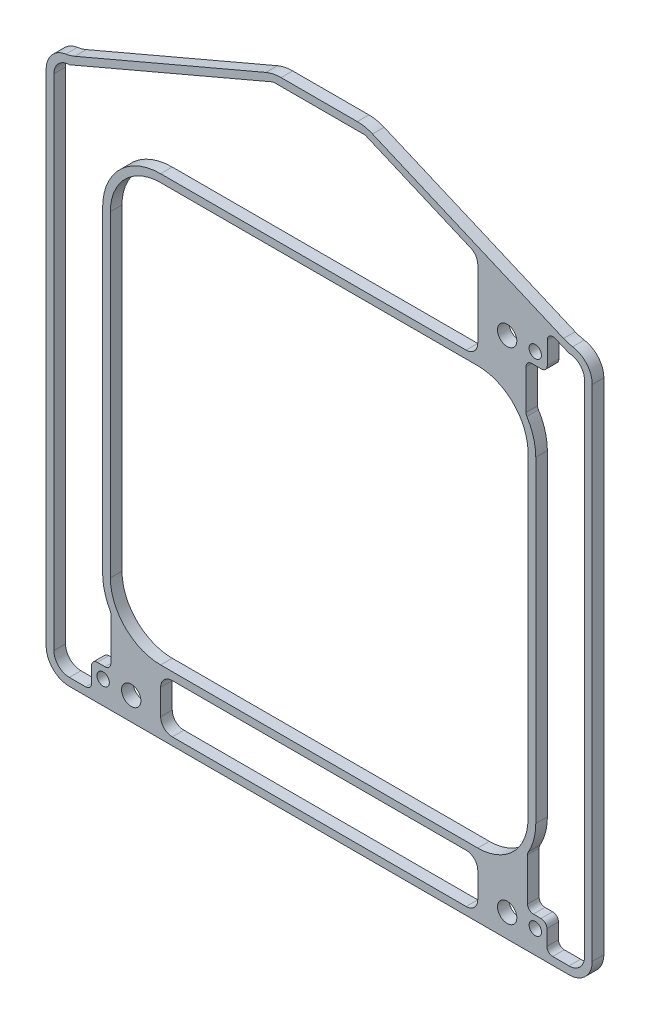
SolidWorks part; units mm, degrees
ref_plane "Front Plane" through (0, 0, 0) normal (0, 0, 1) x (1, 0, 0)
ref_plane "Top Plane" through (0, 0, 0) normal (0, 1, 0) x (1, 0, 0)
ref_plane "Right Plane" through (0, 0, 0) normal (1, 0, 0) x (0, 0, -1)
sketch "Sketch3" plane through (0, 0, 0) normal (0, 0, 1) x (1, 0, 0)
  point P0 (0, 54)
  point P1 (54, 0)
sketch_block_instance "Layer4-1"
sketch_block "Layer4"
sketch "Sketch2" plane through (0, 0, 0) normal (0, 0, 1) x (1, 0, 0)
  line L0 (-6, 91.1) -> (6, 91.1)
  line L1 (41, 56) -> (41, 78.6759)
  line L2 (58.972, 71.0028) -> (58.972, 61.5028)
  line L3 (11.9, 91.1) -> (41, 78.6759)
  line L4 (58.972, 61.5028) -> (53.472, 61.5028)
  line L5 (58.972, 71.0028) -> (64.6, 68.6)
  line L6 (64.6, -68.6) -> (58.87, -68.6)
  line L7 (-41, -56) -> (-41, -68.6)
  line L8 (41, -56) -> (41, -68.6)
  line L9 (53.87, -48.7047) -> (53.87, -61.6)
  line L10 (-53.87, -48.7047) -> (-53.87, -61.6)
  line L11 (41, -68.6) -> (-41, -68.6)
  line L12 (-58.87, -68.6) -> (-64.6, -68.6)
  line L13 (-53.87, -61.6) -> (-58.87, -61.6)
  line L14 (-58.87, -61.6) -> (-58.87, -68.6)
  line L15 (53.87, -61.6) -> (58.87, -61.6)
  line L16 (58.87, -61.6) -> (58.87, -68.6)
  line L17 (53.472, 61.5028) -> (53.472, 49.3336)
  circle A1 centre (48.6, 64.6) radius 2.5
  arc A2 (56, 41) -> (53.472, 49.3336) centre (41, 41) ccw
  arc A5 (56, -41) -> (53.87, -48.7047) centre (41, -41) cw
  arc A6 (-56, -41) -> (-53.87, -48.7047) centre (-41, -41) ccw
  circle A7 centre (48.6, -64.6) radius 2.5
  circle A8 centre (-48.6, -64.6) radius 2.5
  circle A9 centre (55.87, -64.6) radius 1.6
  circle A10 centre (-55.87, -64.6) radius 1.6
  circle A11 centre (55.87, 64.6) radius 1.6
  point P0 (0, 54)
  point P1 (-54, 0)
  point P52 (0, 0)
  line B0 (-6, 91.1) -> (-11.9, 91.1)
  line B1 (-11.9, 91.1) -> (-64.6, 68.6)
  line B2 (-68.6, 64.6) -> (-68.6, -64.6)
  line B3 (68.6, -64.6) -> (68.6, 64.6)
  line B4 (11.9, 91.1) -> (6, 91.1)
  line B5 (-56, 41) -> (-56, -41)
  line B6 (41, 56) -> (-41, 56)
  line B7 (56, -41) -> (56, 41)
  line B8 (-41, -56) -> (41, -56)
  line B9 (-70.6, 64.6) -> (-70.6, -64.6)
  line B10 (-13.7811, 92.2969) -> (-63.1825, 71.2052)
  line B11 (9.8546, 93.1) -> (-9.8546, 93.1)
  line B12 (63.1825, 71.2052) -> (13.7811, 92.2969)
  line B13 (70.6, -64.6) -> (70.6, 64.6)
  line B14 (-64.6, -70.6) -> (64.6, -70.6)
  line B15 (-41, -54) -> (41, -54)
  line B16 (54, -41) -> (54, 41)
  line B17 (41, 54) -> (-41, 54)
  line B18 (-54, 41) -> (-54, -41)
  arc B19 (-64.6, 68.6) -> (-68.6, 64.6) centre (-64.6, 64.6) ccw
  arc B20 (-68.6, -64.6) -> (-64.6, -68.6) centre (-64.6, -64.6) ccw
  arc B21 (64.6, -68.6) -> (68.6, -64.6) centre (64.6, -64.6) ccw
  arc B22 (68.6, 64.6) -> (64.6, 68.6) centre (64.6, 64.6) ccw
  arc B23 (-41, 56) -> (-56, 41) centre (-41, 41) ccw
  arc B24 (-70.6, -64.6) -> (-64.6, -70.6) centre (-64.6, -64.6) ccw
  arc B25 (-65.5409, 70.5258) -> (-70.6, 64.6) centre (-64.6, 64.6) ccw
  arc B26 (-65.5409, 70.5258) -> (-63.1825, 71.2052) centre (-67.1091, 80.402) ccw
  arc B27 (-9.8546, 93.1) -> (-13.7811, 92.2969) centre (-9.8546, 83.1) ccw
  arc B28 (13.7811, 92.2969) -> (9.8546, 93.1) centre (9.8546, 83.1) ccw
  arc B29 (63.1825, 71.2052) -> (65.5409, 70.5258) centre (67.1091, 80.402) ccw
  arc B30 (70.6, 64.6) -> (65.5409, 70.5258) centre (64.6, 64.6) ccw
  arc B31 (64.6, -70.6) -> (70.6, -64.6) centre (64.6, -64.6) ccw
  arc B32 (-54, -41) -> (-41, -54) centre (-41, -41) ccw
  arc B33 (41, -54) -> (54, -41) centre (41, -41) ccw
  arc B34 (54, 41) -> (41, 54) centre (41, 41) ccw
  arc B35 (-41, 54) -> (-54, 41) centre (-41, 41) ccw
  dimension "D1" = 2
  dimension "D2" = 2
  dimension "D3" = 5
  dimension "D4" = 7
  dimension "D5" = 5
  dimension "D6" = 9.5
  dimension "D7" = 5.5
  dimension "D8" = 33.75
sketch_block_instance "Layer2-1"
sketch_block "Layer2"
extrude "Boss-Extrude1" add sketch "Sketch2" along normal blind 3
fillet "Fillet2" radius 1.5 12 edges at (-58.87, -68.6, 1.5) (-58.87, -61.6, 1.5) (-53.87, -61.6, 1.5) (-53.87, -48.7047, 1.5) (58.87, -68.6, 1.5) (58.87, -61.6, 1.5) (53.87, -61.6, 1.5) (53.87, -48.7047, 1.5) (53.472, 49.3336, 1.5) (53.472, 61.5028, 1.5) (58.972, 61.5028, 1.5) (58.972, 71.0028, 1.5)
fillet "Fillet3" radius 3 6 edges at (-41, -68.6, 1.5) (-41, -56, 1.5) (41, -56, 1.5) (41, -68.6, 1.5) (41, 56, 1.5) (41, 78.6759, 1.5)
